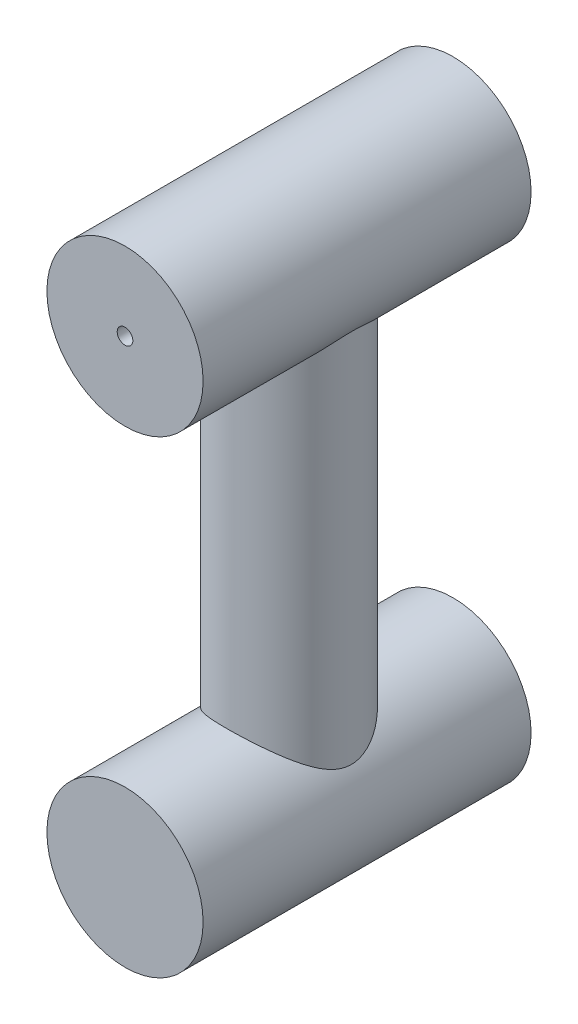
SolidWorks part; units mm, degrees
ref_plane "Front Plane" through (0, 0, 0) normal (0, 0, 1) x (1, 0, 0)
ref_plane "Top Plane" through (0, 0, 0) normal (0, 1, 0) x (1, 0, 0)
ref_plane "Right Plane" through (0, 0, 0) normal (1, 0, 0) x (0, 0, -1)
sketch "Sketch1" plane through (0, 0, 0) normal (0, 0, 1) x (1, 0, 0)
  circle A0 centre (0, 0) radius 25
  dimension "D1" = 50
extrude "Boss-Extrude1" add sketch "Sketch1" against normal mid plane 105
sketch "Sketch2" plane through (0, 0, -52.5) normal (0, 0, -1) x (-1, 0, 0)
  circle A0 centre (0, 0) radius 2.5
  dimension "D1" = 5
extrude "Cut-Extrude1" cut sketch "Sketch2" against normal blind 10
sketch "Sketch3" plane through (0, 0, 0) normal (0, 1, 0) x (1, 0, 0)
  circle A0 centre (0, 0) radius 20
  dimension "D1" = 40
extrude "Boss-Extrude2" add sketch "Sketch3" along normal blind 150
ref_plane "Plane1" through (0, 75, 0) normal (0, 1, 0) x (1, 0, 0)
mirror "Mirror1" about plane through (0, 75, 0) normal (0, 1, 0) of "Cut-Extrude1", "Boss-Extrude1"
sketch "Sketch4" plane through (0, 0, 52.5) normal (0, 0, 1) x (1, 0, 0)
  circle A0 centre (0, 150) radius 2.5
  dimension "D1" = 5
extrude "Cut-Extrude2" cut sketch "Sketch4" against normal blind 5
